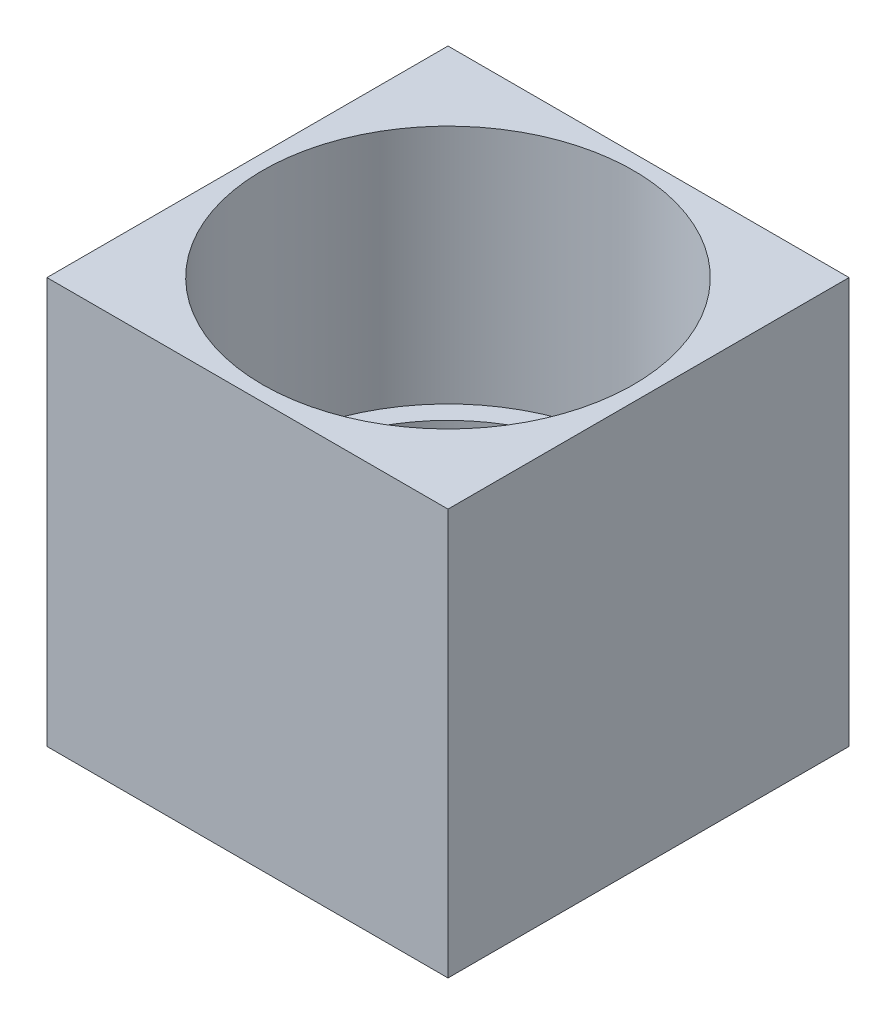
SolidWorks part; units mm, degrees
ref_plane "Front Plane" through (0, 0, 0) normal (0, 0, 1) x (1, 0, 0)
ref_plane "Top Plane" through (0, 0, 0) normal (0, 1, 0) x (1, 0, 0)
ref_plane "Right Plane" through (0, 0, 0) normal (1, 0, 0) x (0, 0, -1)
sketch "Sketch1" plane through (0, 0, 0) normal (0, 1, 0) x (1, 0, 0)
  line L1 (-20, -20) -> (20, -20)
  line L2 (-20, -20) -> (-20, 20)
  line L3 (-20, 20) -> (20, 20)
  line L4 (20, -20) -> (20, 20)
  line L5 (-20, -20) -> (20, 20) construction
  line L6 (-20, 20) -> (20, -20) construction
  point P0 (0, 0)
extrude "Boss-Extrude1" add sketch "Sketch1" along normal blind 90
sketch "Sketch2" plane through (0, 90, 0) normal (0, 1, 0) x (1, 0, 0)
  circle A0 centre (0, 0) radius 18.5
extrude "Cut-Extrude1" cut sketch "Sketch2" against normal blind 45
sketch "Sketch3" plane through (0, 45, 0) normal (0, 1, 0) x (1, 0, 0)
  circle A0 centre (0, 0) radius 16.5
extrude "Cut-Extrude2" cut sketch "Sketch3" against normal blind 41
sketch "Sketch4" plane through (0, 90, 0) normal (0, 1, 0) x (1, 0, 0)
  line L1 (-20, -20) -> (20, -20)
  line L2 (-20, -20) -> (-20, 20)
  line L3 (-20, 20) -> (20, 20)
  line L4 (20, -20) -> (20, 20)
  line L5 (-20, -20) -> (20, 20) construction
  line L6 (-20, 20) -> (20, -20) construction
  point P0 (0, 0)
extrude "Cut-Extrude3" cut sketch "Sketch4" against normal blind 21
sketch "Sketch6" plane through (0, 0, 20) normal (0, 0, 1) x (1, 0, 0)
  line L0 (0, 0) -> (0, 15) construction
  line L2 (-10, 7.5) -> (10, 7.5)
  line L3 (-10, 7.5) -> (-10, 22.5)
  line L4 (-10, 22.5) -> (10, 22.5)
  line L5 (10, 7.5) -> (10, 22.5)
  line L6 (-10, 7.5) -> (10, 22.5) construction
  line L7 (-10, 22.5) -> (10, 7.5) construction
extrude "Cut-Extrude4" cut sketch "Sketch6" against normal through all contours L3 L2 L5 L4
sketch "Sketch8" plane through (-20, 0, 0) normal (-1, 0, 0) x (0, 0, 1)
  line L0 (0, 0) -> (0, 15) construction
  line L2 (-10, 7.5) -> (10, 7.5)
  line L3 (-10, 7.5) -> (-10, 22.5)
  line L4 (-10, 22.5) -> (10, 22.5)
  line L5 (10, 7.5) -> (10, 22.5)
  line L6 (-10, 7.5) -> (10, 22.5) construction
  line L7 (-10, 22.5) -> (10, 7.5) construction
extrude "Cut-Extrude5" cut sketch "Sketch8" against normal through all contours L3 L2 L5 L4
sketch "Sketch11" plane through (0, 0, 20) normal (0, 0, 1) x (1, 0, 0)
  line L0 (0, 0) -> (0, 28.5) construction
  line L1 (-20, 0) -> (20, 0) construction
  line L2 (-20, 28.5) -> (20, 28.5) construction
  line L3 (20, 69) -> (20, 0) construction
  line L4 (-20, 28.5) -> (-20, 15.8) construction
  line L5 (-20, 69) -> (-20, 0) construction
  line L7 (-20, 15.8) -> (20, 15.8) construction
  line L8 (-20, 15.8) -> (-20, 69)
  line L9 (-20, 69) -> (20, 69)
  line L10 (20, 15.8) -> (20, 69)
  line L11 (-20, 28.5) -> (20, 28.5)
  line L12 (-20, 28.5) -> (-20, 0)
  line L13 (-20, 0) -> (20, 0)
  line L14 (20, 28.5) -> (20, 0)
  point P9 (0, 28.5)
extrude "Cut-Extrude8" cut sketch "Sketch11" against normal through all contours L12 L11 L14 L13
